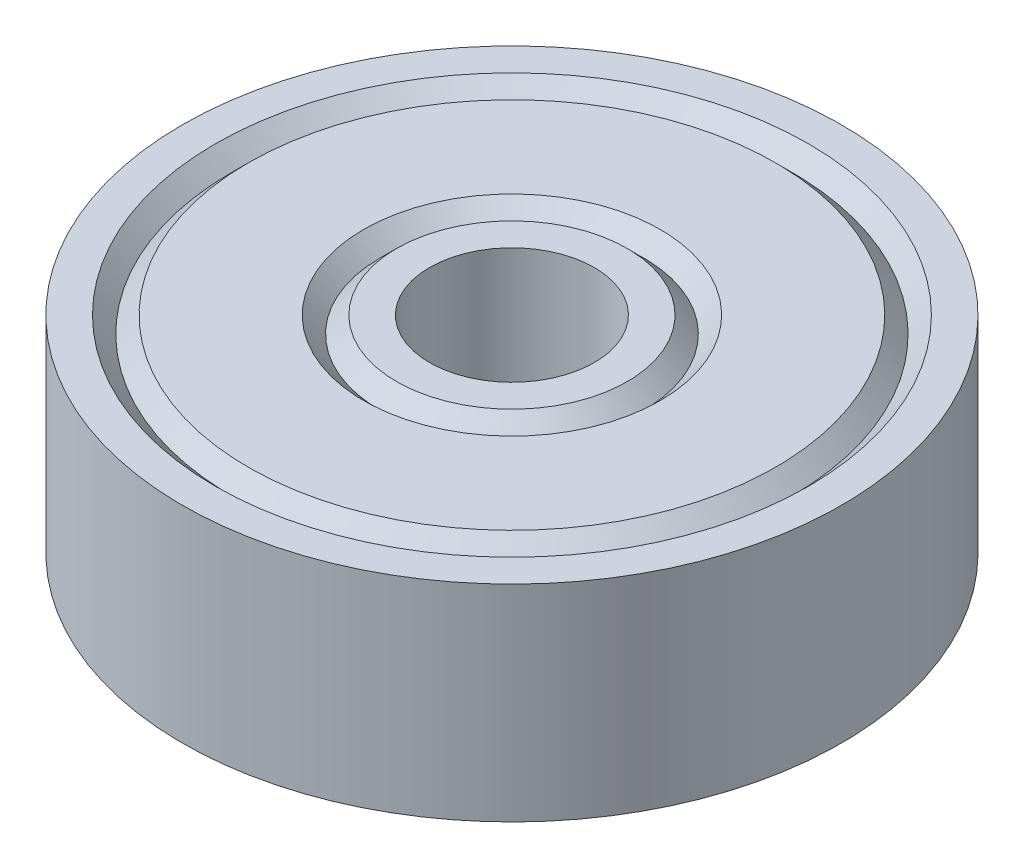
SolidWorks part; units mm, degrees
ref_plane "Front Plane" through (0, 0, 0) normal (0, 0, 1) x (1, 0, 0)
ref_plane "Top Plane" through (0, 0, 0) normal (0, 1, 0) x (1, 0, 0)
ref_plane "Right Plane" through (0, 0, 0) normal (1, 0, 0) x (0, 0, -1)
sketch "Sketch1" plane through (0, 0, 0) normal (0, 0, 1) x (1, 0, 0)
  line L0 (0, 2.5) -> (0, -2.5) construction
  line L1 (-2, 2.5) -> (-2.8, 2.5)
  line L2 (-2, 2.5) -> (-2, -2.5)
  line L3 (-2, -2.5) -> (-2.8, -2.5)
  line L4 (-8, 2.5) -> (-8, -2.5)
  line L5 (-7.2, 2.5) -> (-6.8, 2.1)
  line L6 (-6.8, 2.1) -> (-6.4, 2.5)
  line L7 (-3.6, 2.5) -> (-3.2, 2.1)
  line L8 (-3.2, 2.1) -> (-2.8, 2.5)
  line L9 (-7.2, -2.5) -> (-6.8, -2.1)
  line L10 (-6.8, -2.1) -> (-6.4, -2.5)
  line L11 (-3.6, -2.5) -> (-3.2, -2.1)
  line L12 (-3.2, -2.1) -> (-2.8, -2.5)
  line L13 (-3.6, -2.5) -> (-6.4, -2.5)
  line L14 (-7.2, -2.5) -> (-8, -2.5)
  line L15 (-7.2, 2.5) -> (-8, 2.5)
  line L16 (-3.6, 2.5) -> (-6.4, 2.5)
  line L17 (-6.8, 2.1) -> (-3.2, 2.1) construction
  line L18 (-6.8, 2.1) -> (-6.8, -2.1) construction
  line L19 (-3.2, -2.1) -> (-6.8, -2.1) construction
  line L20 (-3.2, 2.1) -> (-3.2, -2.1) construction
  line L21 (-6.8, 0) -> (-5.6, 0) construction
  line L22 (-2.8, 2.5) -> (-3.6, 2.5) construction
  line L23 (-5.6, 0) -> (-4.4, 0) construction
  line L24 (-6.8, 0) -> (-8, 0) construction
  line L25 (-4.4, 0) -> (-3.2, 0) construction
  line L26 (-3.2, 0) -> (-2, 0) construction
  dimension "D1" = 5
  dimension "D2" = 4
  dimension "D3" = 16
revolve "Revolve1" add sketch "Sketch1" angle 360 about L0
